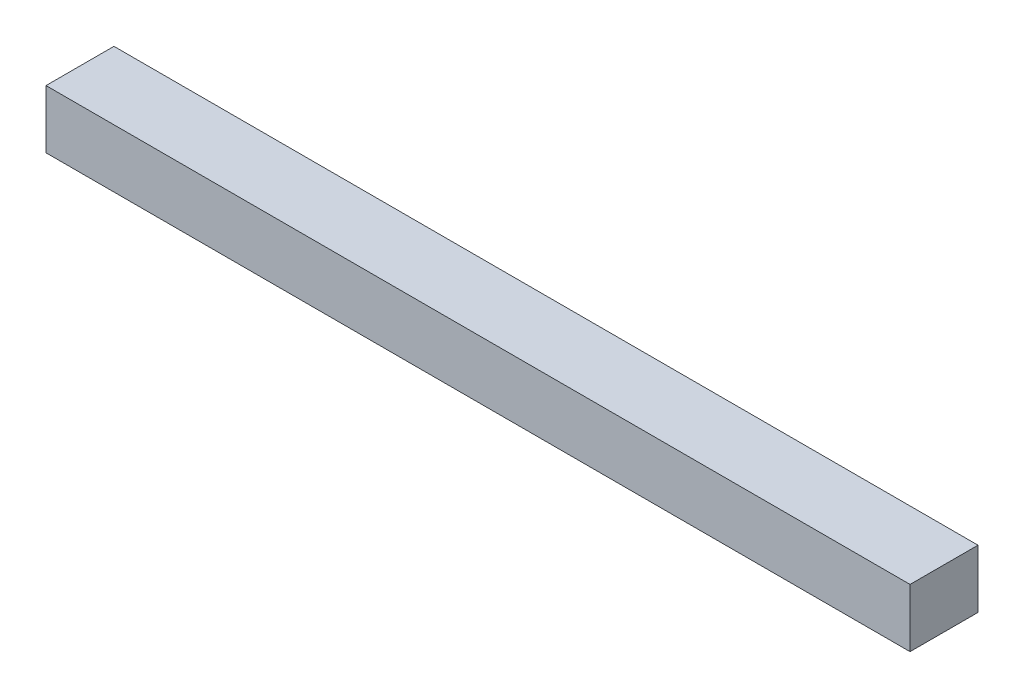
SolidWorks part; units mm, degrees
ref_plane "Front Plane" through (0, 0, 0) normal (0, 0, 1) x (1, 0, 0)
ref_plane "Top Plane" through (0, 0, 0) normal (0, 1, 0) x (1, 0, 0)
ref_plane "Right Plane" through (0, 0, 0) normal (1, 0, 0) x (0, 0, -1)
sketch "Sketch1" plane through (0, -4.2356, 0) normal (0, 1, 0) x (1, 0, 0)
  line L1 (262.47, -79.7622) -> (173.47, -79.7622)
  line L2 (262.47, -79.7622) -> (262.47, -86.7622)
  line L3 (262.47, -86.7622) -> (173.47, -86.7622)
  line L4 (173.47, -79.7622) -> (173.47, -86.7622)
extrude "Boss-Extrude1" add sketch "Sketch1" against normal blind 5 and the other way blind 1
